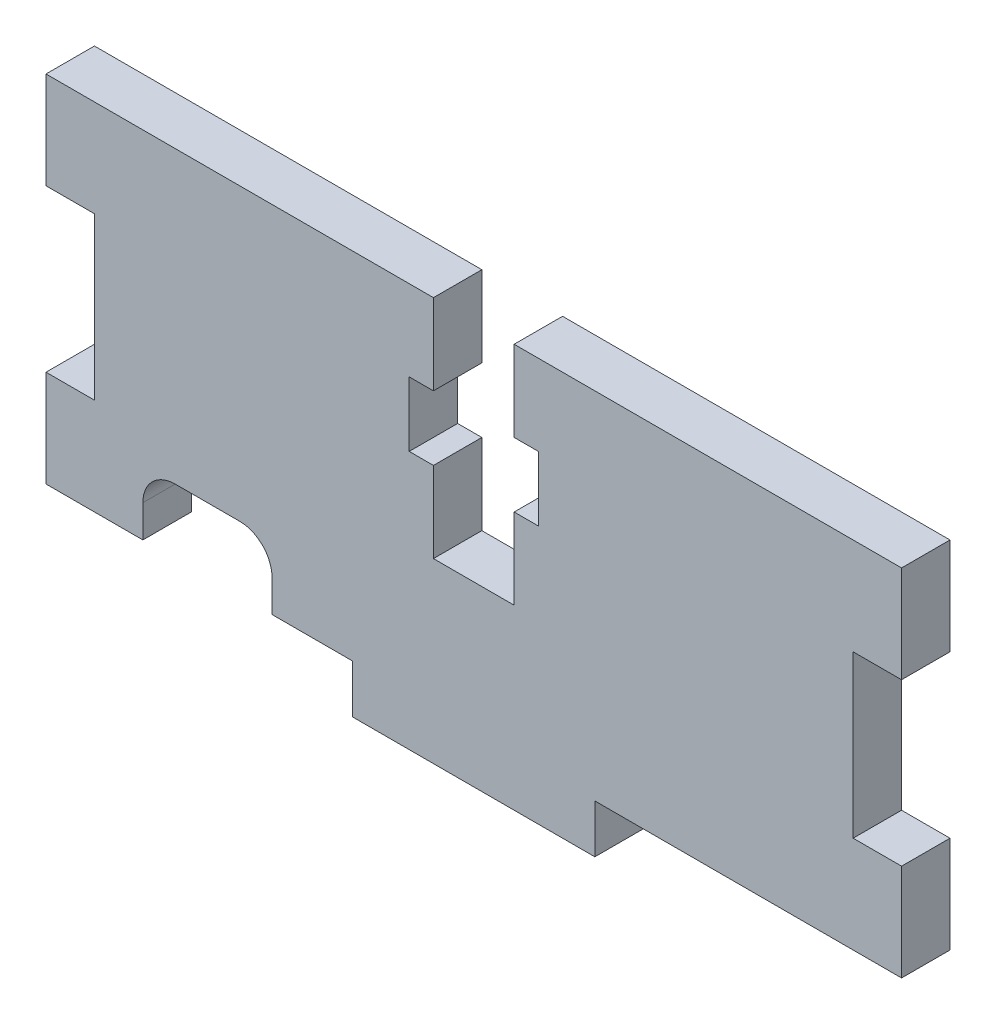
SolidWorks part; units mm, degrees
material "ABS PC"
ref_plane "Front Plane" through (0, 0, 0) normal (0, 0, 1) x (1, 0, 0)
ref_plane "Top Plane" through (0, 0, 0) normal (0, 1, 0) x (1, 0, 0)
ref_plane "Right Plane" through (0, 0, 0) normal (1, 0, 0) x (0, 0, -1)
sketch "Sketch1" plane through (0, 0, 0) normal (0, 0, 1) x (1, 0, 0)
  line L0 (-20, -11) -> (20, -11)
  line L1 (-54, 11) -> (54, 11)
  line L2 (-54, 11) -> (-54, -11)
  line L3 (-54, -11) -> (-35, -11)
  line L4 (54, 11) -> (54, -11)
  line L5 (35, -11) -> (54, -11)
  line L6 (-35, -11) -> (-35, -14)
  line L7 (-35, -14) -> (-20, -14)
  line L8 (-20, -11) -> (-20, -14)
  line L9 (0, 11) -> (0, 0) construction
  line L10 (20, -11) -> (20, -14)
  line L11 (20, -14) -> (35, -14)
  line L12 (35, -11) -> (35, -14)
  line L13 (0, 0) -> (0, -11) construction
  dimension "D1" = 22
  dimension "D2" = 108
  dimension "D3" = 15
  dimension "D4" = 3
  dimension "D5" = 40
extrude "Boss-Extrude1" add sketch "Sketch1" along normal mid plane 3 contours L1 L4 L5 L12 L11 L10 L0 L8 L7 L6 L3 L2
sketch "Sketch2" plane through (0, 0, 1.5) normal (0, 0, 1) x (1, 0, 0)
  line L0 (54, -5) -> (54, 5) construction
  line L1 (1, 5) -> (4, 5)
  line L2 (1, 5) -> (1, -5)
  line L3 (1, -5) -> (4, -5)
  line L4 (4, 5) -> (4, -5)
  line L5 (51, 5) -> (54, 5)
  line L6 (51, 5) -> (51, -5)
  line L7 (51, -5) -> (54, -5)
  line L8 (54, 5) -> (54, -5)
  line L9 (0, 0) -> (1, 0) construction
  dimension "D1" = 3
  dimension "D2" = 47
  dimension "D3" = 10
extrude "Cut-Extrude1" cut sketch "Sketch2" against normal through all
sketch "Sketch3" plane through (0, 0, 1.5) normal (0, 0, 1) x (1, 0, 0)
  line L0 (1, 5) -> (1, -5) construction
  line L1 (-54, 11) -> (1, 11)
  line L2 (-54, 11) -> (-54, -14)
  line L3 (-54, -14) -> (1, -14)
  line L4 (1, 11) -> (1, -14)
  line L5 (-35, -14) -> (-20, -14) construction
extrude "Cut-Extrude2" cut sketch "Sketch3" against normal through all
sketch "Sketch4" plane through (0, 0, -1.5) normal (0, 0, -1) x (-1, 0, 0)
  line L0 (-7, -11) -> (-7, -9)
  line L1 (-1, -11) -> (-20, -11) construction
  line L2 (-9, -7) -> (-13, -7)
  line L3 (-15, -9) -> (-15, -11)
  line L4 (-7, -11) -> (-15, -11)
  line L5 (-20, -11) -> (-20, -14) construction
  arc A0 (-15, -9) -> (-13, -7) centre (-13, -9) cw
  arc A1 (-9, -7) -> (-7, -9) centre (-9, -9) cw
  dimension "D1" = 2
  dimension "D2" = 4
  dimension "D3" = 8
  dimension "D4" = 5
extrude "Cut-Extrude3" cut sketch "Sketch4" against normal through all
sketch "Sketch5" plane through (0, 0, 1.5) normal (0, 0, 1) x (1, 0, 0)
  line L0 (25, 11) -> (25, 6)
  line L1 (1, 11) -> (54, 11) construction
  line L2 (25, 6) -> (23.5, 6)
  line L3 (23.5, 6) -> (23.5, 2)
  line L4 (23.5, 2) -> (25, 2)
  line L5 (25, 2) -> (25, -3)
  line L6 (25, -3) -> (30, -3)
  line L7 (30, -3) -> (30, 2)
  line L8 (30, 2) -> (31.5, 2)
  line L9 (31.5, 2) -> (31.5, 6)
  line L10 (31.5, 6) -> (30, 6)
  line L11 (30, 6) -> (30, 11)
  line L12 (30, 11) -> (25, 11)
  line L13 (27.5, -3) -> (27.5, -14) construction
  line L14 (20, -14) -> (35, -14) construction
  dimension "D1" = 5
  dimension "D2" = 8
  dimension "D3" = 5
  dimension "D4" = 5
  dimension "D5" = 4
extrude "Cut-Extrude4" cut sketch "Sketch5" against normal through all
